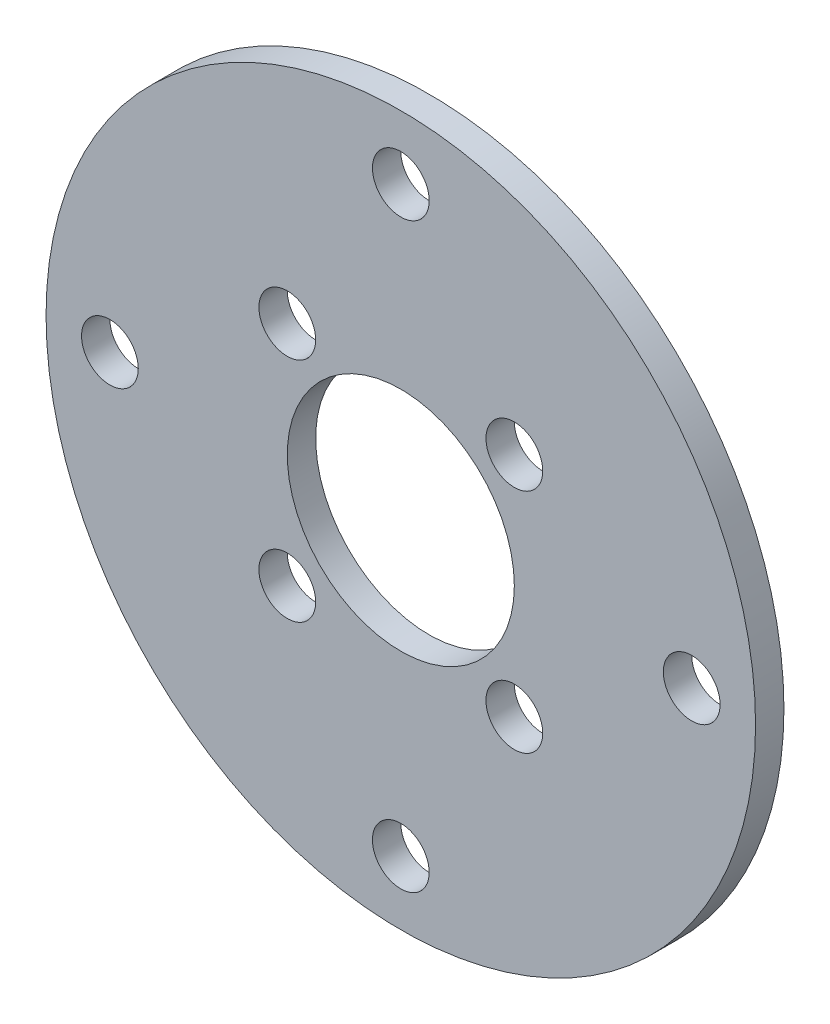
SolidWorks part; units mm, degrees
ref_plane "前视基准面" through (0, 0, 0) normal (0, 0, 1) x (1, 0, 0)
ref_plane "上视基准面" through (0, 0, 0) normal (0, 1, 0) x (1, 0, 0)
ref_plane "右视基准面" through (0, 0, 0) normal (1, 0, 0) x (0, 0, -1)
sketch "Sketch1" plane through (0, 0, 0) normal (0, 0, 1) x (1, 0, 0)
  line L0 (-15.3762, 0) -> (18.3826, 0) construction
  line L1 (0, 13.1951) -> (0, -14.3746) construction
  circle A0 centre (0, 0) radius 25
  circle A6 centre (0, 0) radius 8
  circle A7 centre (-8, 8) radius 2
  circle A8 centre (8, 8) radius 2
  circle A9 centre (8, -8) radius 2
  circle A10 centre (-8, -8) radius 2
  circle A11 centre (0, 0) radius 16 construction
  circle A12 centre (0, 0) radius 20.5 construction
  circle A13 centre (0, 20.5) radius 2
  circle A14 centre (20.5, 0) radius 2
  circle A15 centre (0, -20.5) radius 2
  circle A16 centre (-20.5, 0) radius 2
  dimension "D1" = 16
  dimension "D2" = 50
  dimension "D3" = 8
  dimension "D4" = 8
  dimension "D5" = 8
  dimension "D6" = 8
  dimension "D7" = 4
extrude "Boss-Extrude1" add sketch "Sketch1" along normal blind 2
